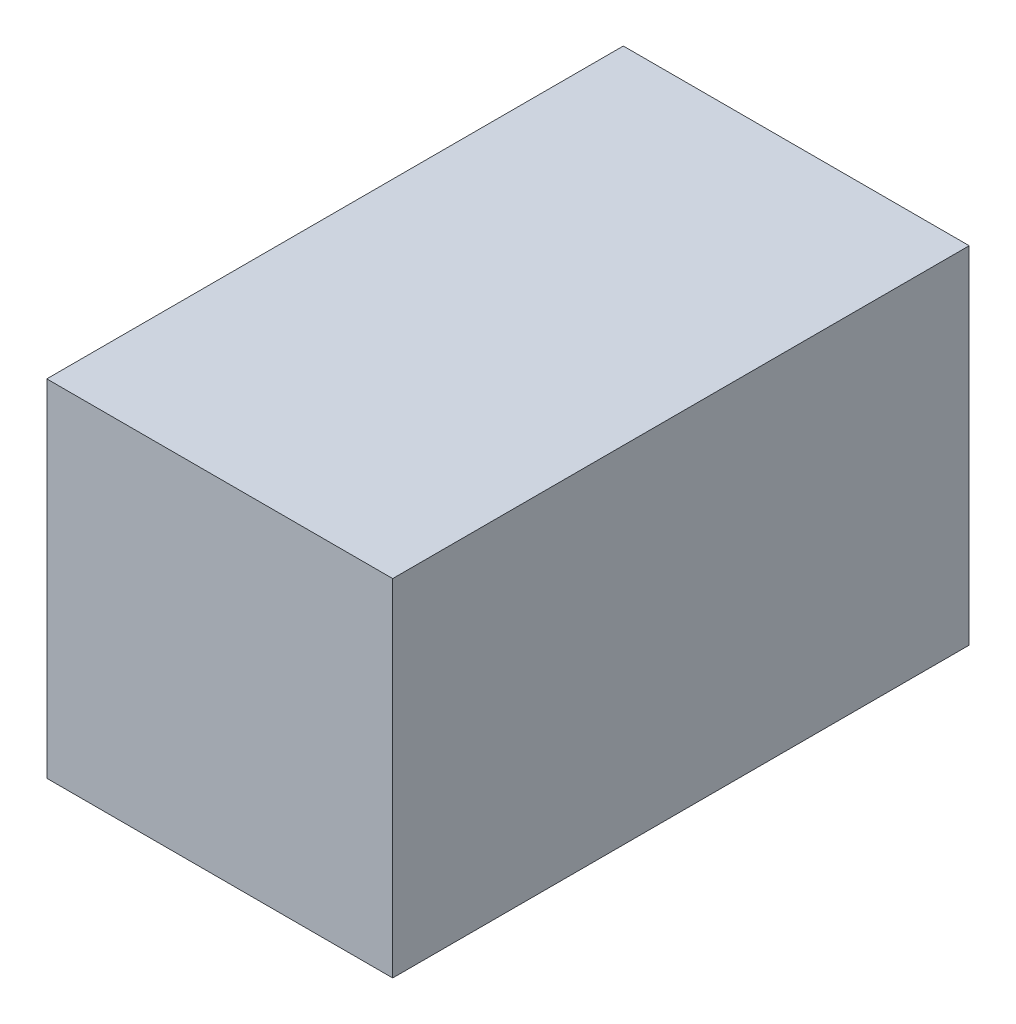
SolidWorks part; units mm, degrees
ref_plane "Alzado" through (0, 0, 0) normal (0, 0, 1) x (1, 0, 0)
ref_plane "Planta" through (0, 0, 0) normal (0, 1, 0) x (1, 0, 0)
ref_plane "Vista lateral" through (0, 0, 0) normal (1, 0, 0) x (0, 0, -1)
sketch "Croquis1" plane through (0, 0, 0) normal (0, 0, 1) x (1, 0, 0)
  line L1 (15, -15) -> (-15, -15)
  line L2 (15, -15) -> (15, 15)
  line L3 (15, 15) -> (-15, 15)
  line L4 (-15, -15) -> (-15, 15)
  line L5 (15, -15) -> (-15, 15) construction
  line L6 (15, 15) -> (-15, -15) construction
  point P0 (0, 0)
  dimension "D1" = 30
  dimension "D2" = 30
extrude "Saliente-Extruir1" add sketch "Croquis1" against normal blind 50
